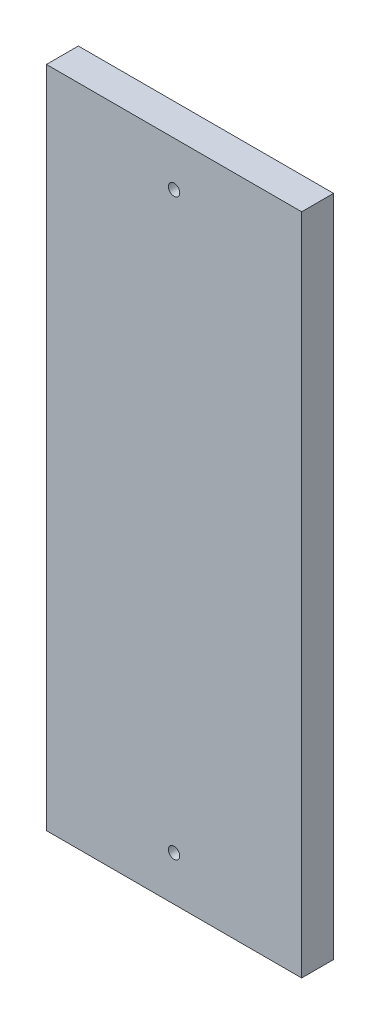
SolidWorks part; units mm, degrees
ref_plane "Front Plane" through (0, 0, 0) normal (0, 0, 1) x (1, 0, 0)
ref_plane "Top Plane" through (0, 0, 0) normal (0, 1, 0) x (1, 0, 0)
ref_plane "Right Plane" through (0, 0, 0) normal (1, 0, 0) x (0, 0, -1)
sketch "Sketch1" plane through (0, 0, 0) normal (0, 1, 0) x (1, 0, 0)
  line L1 (-25.4, 3.175) -> (25.4, 3.175)
  line L2 (-25.4, 3.175) -> (-25.4, -3.175)
  line L3 (-25.4, -3.175) -> (25.4, -3.175)
  line L4 (25.4, 3.175) -> (25.4, -3.175)
  line L5 (-25.4, 3.175) -> (25.4, -3.175) construction
  line L6 (-25.4, -3.175) -> (25.4, 3.175) construction
  point P0 (0, 0)
  dimension "D1" = 50.8
  dimension "D2" = 6.35
extrude "Boss-Extrude1" add sketch "Sketch1" along normal blind 132.08
sketch "Sketch2" plane through (0, 0, 3.175) normal (0, 0, 1) x (1, 0, 0)
  line L0 (-25.4, 66.04) -> (25.4, 66.04) construction
  line L1 (-25.4, 132.08) -> (-25.4, 0) construction
  line L2 (25.4, 132.08) -> (25.4, 0) construction
  line L3 (-31.115, 113.03) -> (29.845, 113.03) construction
  circle A0 centre (0, 123.19) radius 1.1303
  circle A1 centre (0, 8.89) radius 1.1303
  dimension "D2" = 2.2606
  dimension "D1" = 10.16
extrude "Cut-Extrude1" cut sketch "Sketch2" against normal through all
